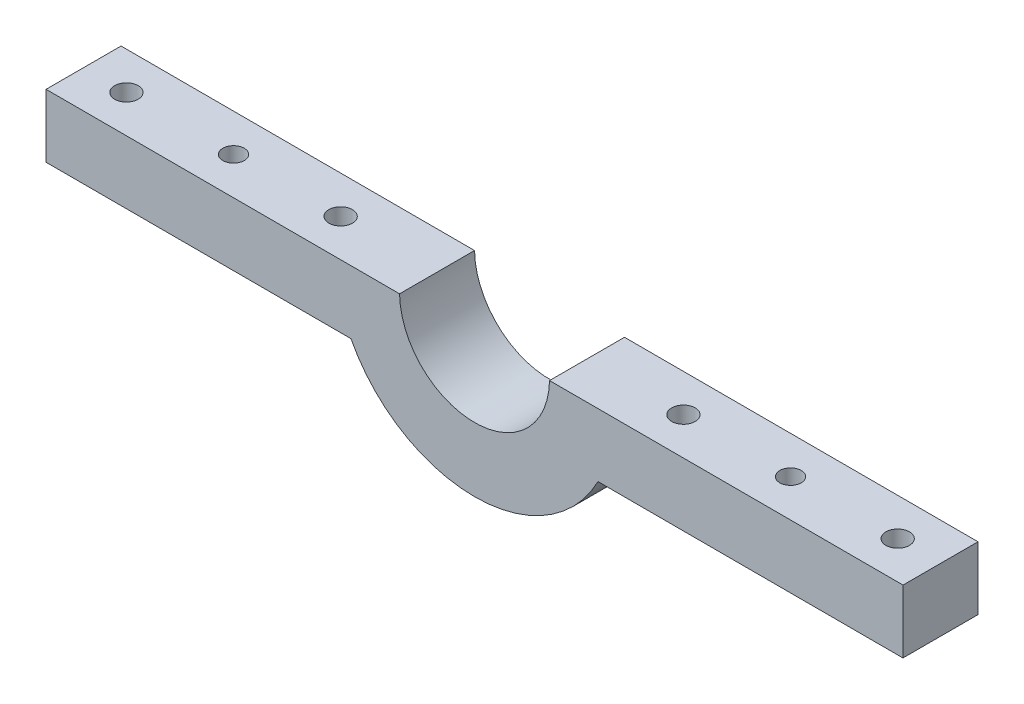
SolidWorks part; units mm, degrees
ref_plane "Plano frontal" through (0, 0, 0) normal (0, 0, 1) x (1, 0, 0)
ref_plane "Plano superior" through (0, 0, 0) normal (0, 1, 0) x (1, 0, 0)
ref_plane "Plano direito" through (0, 0, 0) normal (1, 0, 0) x (0, 0, -1)
sketch "Esboço1" plane through (0, 0, 0) normal (0, 0, 1) x (1, 0, 0)
  line L0 (-199.9977, -240.1091) -> (-34.9942, -240.2728)
  line L3 (200.0021, -240.5058) -> (199.9729, -270.0058)
  line L4 (199.9729, -270.0058) -> (57.6358, -269.8646)
  line L6 (-200.0269, -269.6091) -> (-199.9977, -240.1091)
  line L7 (34.9986, -240.3422) -> (200.0021, -240.5058)
  line L8 (-57.6898, -269.7503) -> (-200.0269, -269.6091)
  arc A1 (-34.9942, -240.2728) -> (34.9986, -240.3422) centre (0.0027, -239.8075) ccw
  arc A3 (-57.6898, -269.7503) -> (57.6358, -269.8646) centre (0.0027, -239.8075) ccw
  dimension "D5" = 35
  dimension "D6" = 65
  dimension "D1" = 200
  dimension "D2" = 400
  dimension "D3" = 0.5
  dimension "D4" = 29.5
  dimension "D7" = 29.5
  dimension "D8" = 0.5
extrude "Ressalto-extrusão1" add sketch "Esboço1" against normal blind 35
hole_wizard "Furo de diâmetro Ø11.0 (11)1" positions "Esboço2" profile "Esboço3" hole size "Ø11.0" standard "DIN" end condition through all
sketch "Esboço2" plane through (-0.2383, -240.3072, 0) normal (0.001, 1, 0) x (1, -0.001, 0)
  line L0 (-34.7559, 0) -> (-199.7595, 0) construction
  line L1 (-199.7595, 35) -> (-199.7595, 0) construction
  line L2 (200.2405, 35) -> (200.2405, 0) construction
  point P0 (-179.7595, 17.5)
  point P2 (-79.7595, 17.5)
  point P4 (80.2405, 17.5)
  point P6 (180.2405, 17.5)
  dimension "D1" = 17.5
  dimension "D2" = 20
  dimension "D3" = 100
  dimension "D4" = 20
  dimension "D5" = 100
sketch "Esboço3" plane through (-179.9977, -240.129, -17.5) normal (0, 0, 1) x (-1, 0.001, 0)
  line L0 (0, 0) -> (0, 64.6983)
  line L1 (0, 64.6983) -> (5.5, 64.6983)
  line L2 (5.5, 64.6983) -> (5.5, 0)
  line L5 (5.5, 0) -> (0, 0)
  line L11 (0, -6.35) -> (0, 107.95) construction
  dimension "Thru Hole Dia." = 11
  dimension "Thru Hole Depth" = 64.6983
hole_wizard "Furos-guia com Ø10.0mm1" positions "Esboço4" profile "Esboço5" hole size "Ø10.0" standard "DIN" end condition through all
sketch "Esboço4" plane through (-0.2676, -269.8072, 0) normal (-0.001, -1, 0) x (-1, 0.001, 0)
  line L0 (199.7595, 35) -> (57.4223, 35) construction
  line L1 (-200.2405, 35) -> (-200.2405, 0) construction
  line L2 (199.7595, 35) -> (199.7595, 0) construction
  point P0 (129.7595, 17.5)
  point P2 (-130.2405, 17.5)
  point P15 (-221.1813, -155.4184)
  dimension "D2" = 70
  dimension "D3" = 70
  dimension "D1" = 17.5
sketch "Esboço5" plane through (-130.027, -269.6785, -17.5) normal (0, 0, 1) x (1, -0.001, 0)
  line L0 (0, 0) -> (0, 29.8967)
  line L1 (0, 29.8967) -> (5, 29.8967)
  line L2 (5, 29.8967) -> (5, 0)
  line L5 (5, 0) -> (0, 0)
  line L11 (0, -6.35) -> (0, 107.95) construction
  dimension "Thru Hole Dia." = 10
  dimension "Thru Hole Depth" = 29.8967
hole_wizard "Furo de diâmetro Ø11.0 (11)2" positions "Esboço6" profile "Esboço7" hole size "Ø11.0" standard "DIN"
sketch "Esboço6" plane through (-0.2676, -269.8072, 0) normal (-0.001, -1, 0) x (-1, 0.001, 0)
  point P0 (129.7595, 17.5)
  point P3 (-130.2405, 17.5)
sketch "Esboço7" plane through (-130.027, -269.6785, -17.5) normal (0, 0, 1) x (1, -0.001, 0)
  line L0 (0, 0) -> (0, 13.3047)
  line L1 (0, 13.3047) -> (5.5, 10)
  line L2 (5.5, 10) -> (5.5, 0)
  line L5 (5.5, 0) -> (0, 0)
  line L10 (0, 13.3047) -> (-5.5, 10) construction
  line L11 (0, -6.35) -> (0, 107.95) construction
  dimension "Hole Dia." = 11
  dimension "Hole Depth" = 10
  dimension "Drill Angle" = 118
